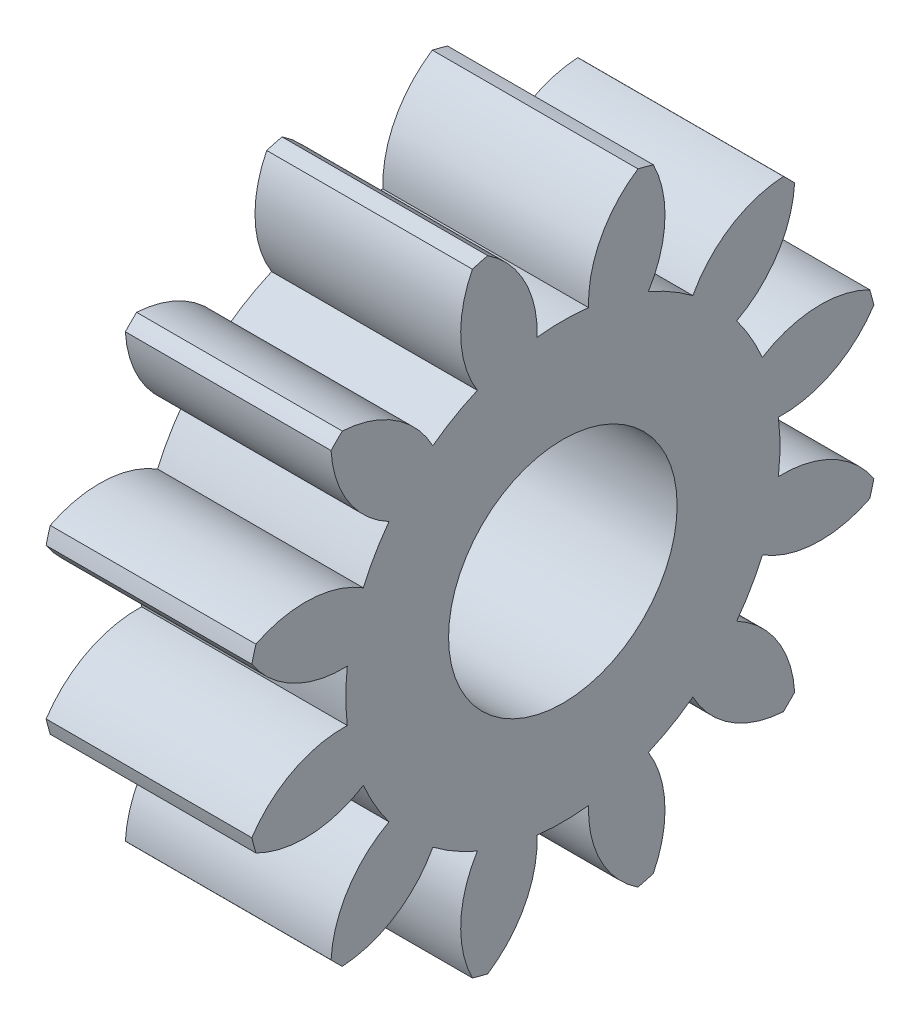
SolidWorks part; units mm, degrees
ref_plane "Plane1" through (0, 0, 0) normal (0, 0, 1) x (1, 0, 0)
ref_plane "Plane2" through (0, 0, 0) normal (0, 1, 0) x (1, 0, 0)
ref_plane "Plane3" through (0, 0, 0) normal (1, 0, 0) x (0, 0, -1)
other "Configuration Table"
sketch "HoldingSke" plane through (0, 0, 0) normal (0, 1, 0) x (1, 0, 0)
  line L0 (0, 0) -> (0.9781, -0.2079)
  line L1 (-15, 0) -> (100, 0) construction
  line L2 (0, 0) -> (-2.1039, 2.3779)
  line L3 (0, 0) -> (-11.863, 4.5341)
  line L4 (0, 0) -> (8.4473, 1.7955)
  line L5 (0, 0) -> (-46.8476, -17.4728)
  line L6 (0, 0) -> (-3.7303, -2.5169)
  line L7 (-2.1039, 2.3779) -> (8.6586, 51.2059)
  line L8 (-76.2, 54.61) -> (-75.3, 54.61)
  line L9 (-71.009, 38.7566) -> (-53.1078, 45.2721)
  line L10 (-76.2, 71.12) -> (104.1128, 71.12)
  line L11 (0, 0) -> (-4.5, 0)
  line L12 (-76.2, 101.6) -> (-76.162, 101.6)
  line L13 (24.9733, 27.94) -> (52.9518, 28.4284)
  line L14 (24.9733, 27.94) -> (24.9743, 27.94)
  line L15 (24.9733, 27.94) -> (100.4006, 29.5858)
  line L16 (-63.627, -1) -> (-12.827, -1)
  circle A0 centre (0, 0) radius 2.5
  circle A1 centre (0, 0) radius 4.749
  circle A2 centre (0, 0) radius 37.5
  circle A3 centre (0, 0) radius 2.5
  dimension "MHD" = 9.498
  dimension "Hub_dia" = 75
  dimension "Bore" = 5
  dimension "MBD" = 5
  dimension "Num_teeth" = 12
  dimension "Pitch" = 1
  dimension "Overall_len" = 50
  dimension "Show_teeth" = 12
  dimension "Thickness" = 4.5
  dimension "OAL" = 50.0001
  dimension "T_dim" = 0.9
  dimension "Ap" = 20
  dimension "H" = 19.05
  dimension "Pitch_radius" = 180.3128
  dimension "Width" = 4.5
  dimension "Backlash" = 0.038
  dimension "Addendum_fac" = 1
  dimension "Dedendum_fac" = 1.25
  dimension "Clearance_fac" = 0.25
  dimension "Dedendum_add" = 0.001
  dimension "Module" = 1
sketch "BasProSke" plane through (0, 0, 0) normal (0, 1, 0) x (1, 0, 0)
  line L0 (-10, 0) -> (60, 0) construction
  line L1 (0, 0) -> (0, 7)
  line L2 (0, 0) -> (4.5, 0)
  line L3 (4.5, 0) -> (4.5, 7)
  line L4 (4.5, 7) -> (0, 7)
  dimension "Thickness" = 4.5
  dimension "Diameter" = 14
revolve "Base-Revolve" add sketch "BasProSke" angle 360 about L0
sketch "TooCutSke" plane through (0, 0, 0) normal (1, 0, 0) x (0, 0, -1)
  line L1 (0, 0) -> (0, 107) construction
  line L2 (0, 0) -> (-0.8496, 5.9395) construction
  line L3 (0, 0) -> (-3.0836, 11.5081) construction
  line L4 (-0.8496, 5.9395) -> (-1.5418, 5.7541) construction
  arc A0 (0.5622, 4.7156) -> (-0.5622, 4.7156) centre (0, 0) ccw
  arc A1 (1.6729, 6.8233) -> (-1.6729, 6.8233) centre (0, 0) ccw
  circle A2 centre (0, 0) radius 6 construction
  circle A3 centre (0, 0) radius 5.6382 construction
  arc A4 (-0.5622, 4.7156) -> (-1.6729, 6.8233) centre (-2.9608, 4.7982) ccw
  arc A5 (1.6729, 6.8233) -> (0.5622, 4.7156) centre (2.9608, 4.7982) ccw
  dimension "Root_dia" = 9.498
  dimension "Overcut_dia" = 14.0508
  dimension "Pitch_dia" = 12
  dimension "Base_dia" = 11.2763
  dimension "Flank_rad" = 2.4
  dimension "Half_ang" = 15
  dimension "Half_CT" = 0.7167
extrude "ToothCut" cut sketch "TooCutSke" along normal through all
fillet "Breaks" [suppressed] radius 0.02
fillet "RootFillets" [suppressed] radius 0.251
pattern_circular "TeethCuts" count 12 every 30 about axis through (-10, 0, 0) along (1, 0, 0) of "ToothCut", "RootFillets", "Breaks"
sketch "HubNeaOneSke" plane through (0, 0, 0) normal (-1, 0, 0) x (0, 0, 1)
  circle A0 centre (0, 0) radius 4.749
  dimension "Diameter" = 9.498
extrude "HubNearOne" [suppressed] add sketch "HubNeaOneSke" along normal blind 45.5001
sketch "HubNeaBotSke" plane through (0, 0, 0) normal (-1, 0, 0) x (0, 0, 1)
  circle A0 centre (0, 0) radius 4.749
  dimension "Diameter" = 9.498
extrude "HubNearBoth" [suppressed] add sketch "HubNeaBotSke" along normal blind 22.75
ref_plane "FarPln" through (4.5, 0, 0) normal (1, 0, 0) x (0, 0, -1)
sketch "HubFarSke" plane through (4.5, 0, 0) normal (1, 0, 0) x (0, 0, -1)
  circle A0 centre (0, 0) radius 4.749
  dimension "Diameter" = 9.498
extrude "HubFar" [suppressed] add sketch "HubFarSke" along normal blind 22.75
sketch "BorSke" plane through (0, 0, 0) normal (1, 0, 0) x (0, 0, -1)
  circle A0 centre (0, 0) radius 2.5
  dimension "Diameter" = 5
extrude "Bore" cut sketch "BorSke" along normal mid plane 100.0001
sketch "KeySke" plane through (0, 0, 0) normal (1, 0, 0) x (0, 0, -1)
  line L0 (-1, 0) -> (-1, 3.4)
  line L1 (-1, 3.4) -> (1, 3.4)
  line L2 (1, 3.4) -> (1, 0)
  line L3 (0, 0) -> (0, 34) construction
  line L4 (-1, 0) -> (1, 0)
  dimension "Offset" = 3.4
  dimension "Width" = 2
extrude "Keyway" [suppressed] cut sketch "KeySke" along normal mid plane 100.0001
pattern_circular "Keyway2" [suppressed] count 2 every 90 about axis through (-10, 0, 0) along (1, 0, 0)
equation "' \"Module@HoldingSke\" = 6.35"
equation "' \"Num_teeth@HoldingSke\" = 12"
equation "' \"Ap@HoldingSke\" =  20"
equation "' \"Ap@HoldingSke\" = 20"
equation "' \"Width@HoldingSke\" = 0.5 * 25.4"
equation "' \"Hub_dia@HoldingSke\"= 1 * 25.4"
equation "' \"Hub_dia@HoldingSke\" = 1 * 25.4"
equation "' \"Overall_len@HoldingSke\" = 1.0 * 25.4"
equation "' \"Bore@HoldingSke\" = 0.75 * 25.4"
equation "' \"T_dim@HoldingSke\" = 0.1 * 25.4"
equation "' \"Width@KeySke\" = 0.25 * 25.4"
equation "' \"Show_teeth@HoldingSke\" = 13"
equation "' \"Backlash@HoldingSke\" = 0.009 * 25.4"
equation "' \"Addendum_fac@HoldingSke\" = 1.0"
equation "' \"Dedendum_fac@HoldingSke\" = 1.25"
equation "' \"Dedendum_add@HoldingSke\" = 0.00005 * 25.4"
equation "' \"Clearance_fac@HoldingSke\" = 0.25"
equation "\"Pitch@HoldingSke\" = 1 / \"Module@HoldingSke\""
equation "\"Overcut_dia@TooCutSke\" = (\"Num_teeth@HoldingSke\" + 2 * \"Addendum_fac@HoldingSke\") / \"Pitch@HoldingSke\" + 0.002 * 25.4"
equation "\"Pitch_dia@TooCutSke\" = \"Num_teeth@HoldingSke\" / \"Pitch@HoldingSke\""
equation "\"Base_dia@TooCutSke\" = \"Num_teeth@HoldingSke\" / \"Pitch@HoldingSke\" * cos((\"Ap@HoldingSke\"  * 3.14159265 / 180))"
equation "\"Root_dia@TooCutSke\" = (\"Num_teeth@HoldingSke\" + 2) / \"Pitch@HoldingSke\" - 2 * (\"Addendum_fac@HoldingSke\" + \"Dedendum_fac@HoldingSke\") / \"Pitch@HoldingSke\" - \"Dedendum_add@HoldingSke\" * 2"
equation "\"Half_ang@TooCutSke\" = 180 / \"Num_teeth@HoldingSke\""
equation "\"Half_CT@TooCutSke\" = \"Num_teeth@HoldingSke\" / \"Pitch@HoldingSke\" * sin((3.14159265 / 2 / \"Num_teeth@HoldingSke\")) / 2 - 7 * \"Backlash@HoldingSke\" / 4"
equation "\"Flank_rad@TooCutSke\" = \"Num_teeth@HoldingSke\" / \"Pitch@HoldingSke\" / 5"
equation "\"Radius@RootFillets\" = \"Clearance_fac@HoldingSke\" / \"Pitch@HoldingSke\" + \"Dedendum_add@HoldingSke\""
equation "\"Break_rad@Breaks\" = 0.02 / \"Pitch@HoldingSke\""
equation "\"Thickness@HoldingSke\" = \"Width@HoldingSke\""
equation "\"OAL@HoldingSke\" = \"Thickness@HoldingSke\""
equation "\"MHD@HoldingSke\" = (\"Num_teeth@HoldingSke\" + 2) / \"Pitch@HoldingSke\" - 2 * (\"Addendum_fac@HoldingSke\" + \"Dedendum_fac@HoldingSke\")  / \"Pitch@HoldingSke\" - \"Dedendum_add@HoldingSke\" * 2"
equation "\"MBD@HoldingSke\" = (\"Num_teeth@HoldingSke\" + 2) / \"Pitch@HoldingSke\" - 2 * (\"Addendum_fac@HoldingSke\" + \"Dedendum_fac@HoldingSke\")  / \"Pitch@HoldingSke\" - \"Dedendum_add@HoldingSke\" * 2 - 0.002 * 25.4"
equation "\"MHD@HoldingSke\" = ((sgn( \"MHD@HoldingSke\" - \"Hub_dia@HoldingSke\" )-1)*( \"MHD@HoldingSke\" - \"Hub_dia@HoldingSke\" ))/-2+ \"Hub_dia@HoldingSke\""
equation "\"MBD@HoldingSke\" = ((sgn( \"MBD@HoldingSke\" - \"Bore@HoldingSke\" )-1)*( \"MBD@HoldingSke\" - \"Bore@HoldingSke\" ))/-2+ \"Bore@HoldingSke\""
equation "\"OAL@HoldingSke\" = ((sgn( \"OAL@HoldingSke\" - \"Overall_len@HoldingSke\" )+1)*( \"OAL@HoldingSke\" - \"Overall_len@HoldingSke\" ))/2 + \"Overall_len@HoldingSke\" + 0.000002 * 25.4"
equation "\"Num_teeth@TeethCuts\" = int( \"Show_teeth@HoldingSke\" ) + 1"
equation "\"Num_teeth@TeethCuts\" = ((sgn( \"Num_teeth@TeethCuts\" - \"Num_teeth@HoldingSke\" )-1)*( \"Num_teeth@TeethCuts\" - \"Num_teeth@HoldingSke\" ))/-2+ \"Num_teeth@HoldingSke\""
equation "\"Num_teeth@TeethCuts\" = ((sgn( \"Num_teeth@TeethCuts\" - 2.0)+1)*( \"Num_teeth@TeethCuts\" - 2.0))/2 +2.0"
equation "\"Angle@TeethCuts\" = 360.0 / \"Num_teeth@HoldingSke\""
equation "\"Diameter@BasProSke\" = (\"Num_teeth@HoldingSke\" + 2 * \"Addendum_fac@HoldingSke\") / \"Pitch@HoldingSke\""
equation "\"Thickness@BasProSke\"  = \"Thickness@HoldingSke\""
equation "' \"Fillet_rad@BasProSke\" =  \"Thickness@HoldingSke\" * 0.05"
equation "' \"Fillet_rad@BasProSke\" = \"Thickness@HoldingSke\" * 0.05"
equation "\"MHD@HoldingSke\" = ((sgn( \"MHD@HoldingSke\" - \"Root_dia@TooCutSke\" )-1)*( \"MHD@HoldingSke\" - \"Root_dia@TooCutSke\" ))/-2+ \"Root_dia@TooCutSke\""
equation "\"Diameter@HubNeaOneSke\" = \"MHD@HoldingSke\""
equation "\"Length@HubNearOne\" = \"OAL@HoldingSke\" - \"Thickness@BasProSke\""
equation "\"Diameter@HubNeaBotSke\" = \"MHD@HoldingSke\""
equation "\"Length@HubNearBoth\" = ( \"OAL@HoldingSke\" - \"Thickness@BasProSke\" ) / 2.0"
equation "\"Thickness@FarPln\" = \"Thickness@BasProSke\""
equation "\"Diameter@HubFarSke\" = \"MHD@HoldingSke\""
equation "\"Length@HubFar\" = ( \"OAL@HoldingSke\" - \"Thickness@BasProSke\" ) / 2.0"
equation "\"Diameter@BorSke\" = \"MBD@HoldingSke\""
equation "\"D1@Bore\" = \"OAL@HoldingSke\" * 2.0"
equation "\"D1@Keyway\" = \"OAL@HoldingSke\" * 2.0"
equation "\"Offset@KeySke\" = \"T_dim@HoldingSke\" + \"MBD@HoldingSke\" / 2.0"
